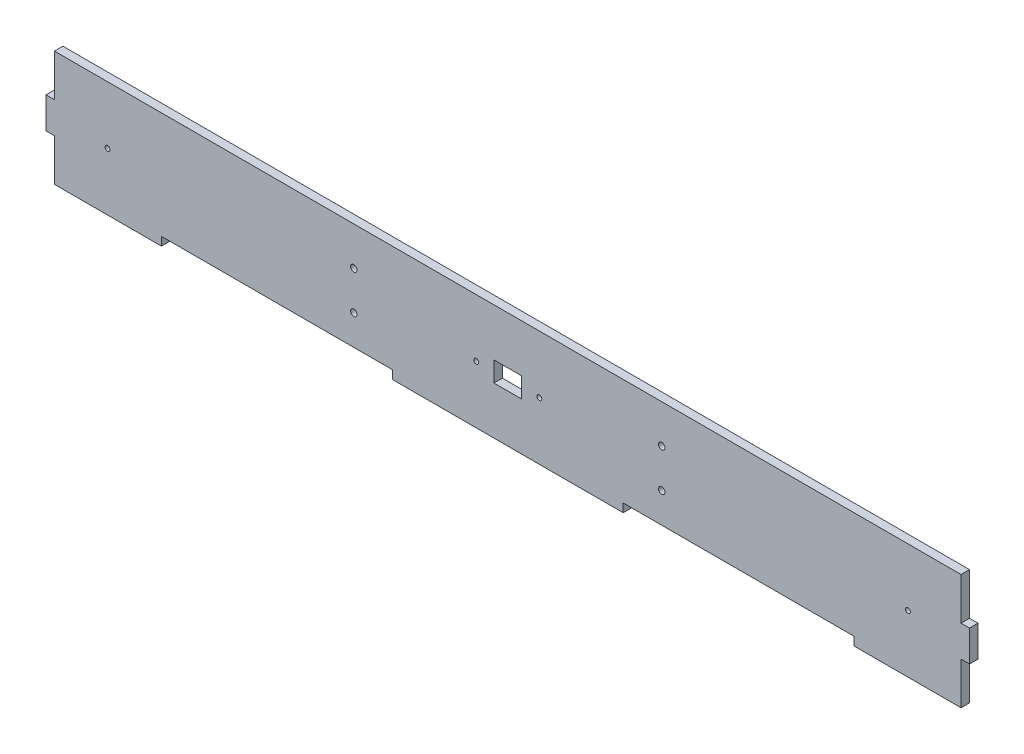
SolidWorks part; units mm, degrees
ref_plane "Front Plane" through (0, 0, 0) normal (0, 0, 1) x (1, 0, 0)
ref_plane "Top Plane" through (0, 0, 0) normal (0, 1, 0) x (1, 0, 0)
ref_plane "Right Plane" through (0, 0, 0) normal (1, 0, 0) x (0, 0, -1)
sketch "Sketch1" plane through (0, 0, 0) normal (0, 0, 1) x (1, 0, 0)
  line L0 (308.5, 78) -> (308.5, 50.625)
  line L1 (308.5, 50.625) -> (303, 50.625)
  line L2 (303, 50.625) -> (303, 42.125)
  line L3 (303, 42.125) -> (306.25, 42.125)
  line L4 (306.25, 42.125) -> (306.25, 40.5)
  line L5 (306.25, 40.5) -> (306.25, 38.875)
  line L6 (306.25, 38.875) -> (303, 38.875)
  line L7 (303, 38.875) -> (303, 30.375)
  line L8 (303, 30.375) -> (308.5, 30.375)
  line L9 (308.5, 30.375) -> (308.5, 3)
  line L10 (308.5, 3) -> (378, 3)
  line L11 (378, 3) -> (378, 8.5)
  line L12 (378, 8.5) -> (451.375, 8.5)
  line L13 (451.375, 8.5) -> (451.375, 17.95)
  line L14 (451.375, 17.95) -> (450.125, 17.95)
  line L15 (450.125, 17.95) -> (450.125, 20.6)
  line L16 (450.125, 20.6) -> (451.375, 20.6)
  line L17 (451.375, 20.6) -> (451.375, 23.25)
  line L18 (451.375, 23.25) -> (454.625, 23.25)
  line L19 (454.625, 23.25) -> (454.625, 20.6)
  line L20 (454.625, 20.6) -> (455.875, 20.6)
  line L21 (455.875, 20.6) -> (455.875, 17.95)
  line L22 (455.875, 17.95) -> (454.625, 17.95)
  line L23 (454.625, 17.95) -> (454.625, 8.5)
  line L24 (454.625, 8.5) -> (528, 8.5)
  line L25 (528, 8.5) -> (528, 3)
  line L26 (528, 3) -> (678, 3)
  line L27 (678, 3) -> (678, 8.5)
  line L28 (678, 8.5) -> (751.375, 8.5)
  line L29 (751.375, 8.5) -> (751.375, 17.95)
  line L30 (751.375, 17.95) -> (750.125, 17.95)
  line L31 (750.125, 17.95) -> (750.125, 20.6)
  line L32 (750.125, 20.6) -> (751.375, 20.6)
  line L33 (751.375, 20.6) -> (751.375, 23.25)
  line L34 (751.375, 23.25) -> (754.625, 23.25)
  line L35 (754.625, 23.25) -> (754.625, 20.6)
  line L36 (754.625, 20.6) -> (755.875, 20.6)
  line L37 (755.875, 20.6) -> (755.875, 17.95)
  line L38 (755.875, 17.95) -> (754.625, 17.95)
  line L39 (754.625, 17.95) -> (754.625, 8.5)
  line L40 (754.625, 8.5) -> (828, 8.5)
  line L41 (828, 8.5) -> (828, 3)
  line L42 (828, 3) -> (897.5, 3)
  line L43 (897.5, 3) -> (897.5, 30.375)
  line L44 (897.5, 30.375) -> (903, 30.375)
  line L45 (903, 30.375) -> (903, 38.875)
  line L46 (903, 38.875) -> (899.75, 38.875)
  line L47 (899.75, 38.875) -> (899.75, 40.5)
  line L48 (899.75, 40.5) -> (899.75, 42.125)
  line L49 (899.75, 42.125) -> (903, 42.125)
  line L50 (903, 42.125) -> (903, 50.625)
  line L51 (903, 50.625) -> (897.5, 50.625)
  line L52 (897.5, 50.625) -> (897.5, 78)
  line L53 (897.5, 78) -> (308.5, 78)
extrude "Boss-Extrude1" add sketch "Sketch1" along normal blind 5.5
sketch "Sketch2" plane through (0, 0, 5.5) normal (0, 0, 1) x (1, 0, 0)
  line L0 (582.5, 40.5) -> (623.5, 40.5)
  line L1 (897.5, 78) -> (308.5, 78) construction
  line L2 (306.25, 42.125) -> (306.25, 38.875) construction
  line L4 (594, 47) -> (612, 47)
  line L5 (594, 47) -> (594, 34)
  line L6 (594, 34) -> (612, 34)
  line L7 (612, 47) -> (612, 34)
  circle A0 centre (582.5, 40.5) radius 1.6
  circle A1 centre (623.5, 40.5) radius 1.6
  point P4 (603, 40.5)
  point P7 (603, 78)
  point P8 (612, 40.5)
  point P11 (306.25, 40.5)
  point P16 (603, 47)
  dimension "D1" = 3.2
  dimension "D2" = 41
  dimension "D3" = 13
  dimension "D4" = 18
extrude "Cut-Extrude1" cut sketch "Sketch2" against normal through all both and the other way through all
sketch "Sketch3" plane through (0, 0, 5.5) normal (0, 0, 1) x (1, 0, 0)
  line L1 (503, 53) -> (703, 53)
  line L2 (503, 53) -> (503, 28)
  line L3 (503, 28) -> (703, 28)
  line L4 (703, 53) -> (703, 28)
  line L5 (897.5, 78) -> (308.5, 78) construction
  circle A0 centre (503, 53) radius 2.1
  circle A1 centre (503, 28) radius 2.1
  circle A2 centre (703, 28) radius 2.1
  circle A3 centre (703, 53) radius 2.1
  point P4 (603, 53)
  point P7 (603, 78)
  dimension "D4" = 4.2
  dimension "D1" = 25
  dimension "D2" = 200
  dimension "D3" = 25
extrude "Cut-Extrude2" cut sketch "Sketch3" against normal through all contours A0 | A1 | A2 | A3
sketch "Sketch4" plane through (0, 0, 5.5) normal (0, 0, 1) x (1, 0, 0)
  line L0 (306.25, 42.125) -> (306.25, 38.875) construction
  line L1 (303, 50.625) -> (303, 42.125) construction
  line L2 (903, 42.125) -> (903, 50.625) construction
  circle A0 centre (343, 40.5) radius 1.6
  circle A1 centre (863, 40.5) radius 1.6
  point P7 (306.25, 40.5)
  dimension "D3" = 3.2
  dimension "D1" = 40
  dimension "D2" = 40
extrude "Cut-Extrude3" cut sketch "Sketch4" against normal through all
sketch "Sketch5" plane through (0, 0, 5.5) normal (0, 0, 1) x (1, 0, 0)
  line L1 (303, 42.125) -> (306.25, 42.125)
  line L2 (303, 42.125) -> (303, 38.875)
  line L3 (303, 38.875) -> (306.25, 38.875)
  line L4 (306.25, 42.125) -> (306.25, 38.875)
  line L5 (451.375, 23.25) -> (454.625, 23.25)
  line L6 (451.375, 23.25) -> (451.375, 8.5)
  line L7 (451.375, 8.5) -> (454.625, 8.5)
  line L8 (454.625, 23.25) -> (454.625, 8.5)
  line L9 (450.125, 20.6) -> (455.875, 20.6)
  line L10 (450.125, 20.6) -> (450.125, 17.95)
  line L11 (450.125, 17.95) -> (455.875, 17.95)
  line L12 (455.875, 20.6) -> (455.875, 17.95)
  line L13 (903, 42.125) -> (899.75, 42.125)
  line L14 (903, 42.125) -> (903, 38.875)
  line L15 (903, 38.875) -> (899.75, 38.875)
  line L16 (899.75, 42.125) -> (899.75, 38.875)
  line L17 (751.375, 23.25) -> (754.625, 23.25)
  line L18 (751.375, 23.25) -> (751.375, 8.5)
  line L19 (751.375, 8.5) -> (754.625, 8.5)
  line L20 (754.625, 23.25) -> (754.625, 8.5)
  line L21 (750.125, 20.6) -> (755.875, 20.6)
  line L22 (750.125, 20.6) -> (750.125, 17.95)
  line L23 (750.125, 17.95) -> (755.875, 17.95)
  line L24 (755.875, 20.6) -> (755.875, 17.95)
extrude "Boss-Extrude2" add sketch "Sketch5" against normal up to surface (5.5 mm away) contours L23 L18 L19 L20 | L18 L23 L20 L21 | L22 L23 L18 L21 | L18 L21 L20 L17 | L24 L21 L20 L23 | L13 L16 L15 L14 | L11 L6 L7 L8 | L6 L11 L8 L9 | L6 L9 L8 L5 | L10 L11 L6 L9 | L12 L9 L8 L11 | L4 L1 L2 L3 up to face at (344.6, 40.5, 0)
